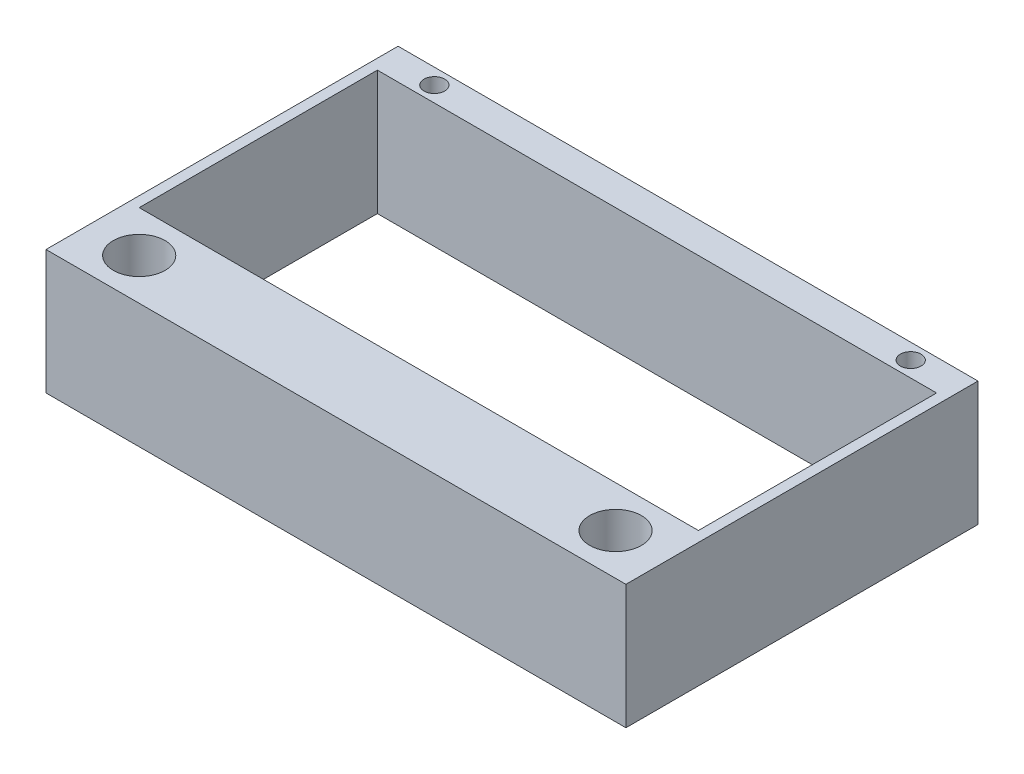
SolidWorks part; units mm, degrees
ref_plane "前视基准面" through (0, 0, 0) normal (0, 0, 1) x (1, 0, 0)
ref_plane "上视基准面" through (0, 0, 0) normal (0, 1, 0) x (1, 0, 0)
ref_plane "右视基准面" through (0, 0, 0) normal (1, 0, 0) x (0, 0, -1)
other "Configuration Table"
sketch "草图2" plane through (0, 0, 0) normal (0, 1, 0) x (1, 0, 0)
  line L0 (-10.7257, 9.9292) -> (45.2743, 9.9292)
  line L1 (45.2743, 9.9292) -> (45.2743, -22.0708)
  line L2 (45.2743, -22.0708) -> (-10.7257, -22.0708)
  line L3 (-10.7257, -22.0708) -> (-10.7257, -7.0708)
  line L5 (-9.7257, -7.0708) -> (-9.7257, -14.0708)
  line L6 (-9.7257, -14.0708) -> (44.2743, -14.0708)
  line L7 (44.2743, -14.0708) -> (44.2743, 8.9292)
  line L8 (44.2743, 8.9292) -> (-9.7257, 8.9292)
  line L9 (-9.7257, 8.9292) -> (-9.7257, 0.9292)
  line L11 (-10.7257, 1.9292) -> (-10.7257, 9.9292)
  line L12 (-10.7257, 1.9292) -> (-10.7257, -7.0708)
  line L13 (-9.7257, -7.0708) -> (-9.7257, 0.9292)
  dimension "D1" = 1
  dimension "D2" = 56
  dimension "D3" = 32
  dimension "D4" = 8
  dimension "D5" = 1
  dimension "D7" = 54
extrude "凸台-拉伸1" add sketch "草图2" along normal blind 12
ref_plane "基准面1" through (0, 12, 0) normal (0, 1, 0) x (1, 0, 0)
sketch "草图4" plane through (0, 0, 0) normal (0, 1, 0) x (1, 0, 0)
  line L1 (-10.7257, 9.9292) -> (45.2743, 9.9292)
  line L2 (-10.7257, 9.9292) -> (-10.7257, 11.9292)
  line L3 (-10.7257, 11.9292) -> (45.2743, 11.9292)
  line L4 (45.2743, 9.9292) -> (45.2743, 11.9292)
  dimension "D1" = 2
extrude "凸台-拉伸2" add sketch "草图4" along normal blind 12
sketch "草图3" plane through (0, 12, 0) normal (0, 1, 0) x (1, 0, 0)
  line L0 (-10.7257, 11.9292) -> (-10.7257, -22.0708) construction
  line L9 (45.2743, 11.9292) -> (-10.7257, 11.9292) construction
  line L10 (45.2743, -22.0708) -> (45.2743, 11.9292) construction
  line L12 (-10.7257, -22.0708) -> (45.2743, -22.0708) construction
  line L13 (-3.876, -14.0708) -> (-3.876, -22.0708) construction
  line L14 (-9.7257, -14.0708) -> (44.2743, -14.0708) construction
  line L15 (-3.876, -18.0708) -> (-9.3766, -18.0708) construction
  line L16 (-10.7257, 11.9292) -> (-10.7257, -22.0708) construction
  line L17 (45.2743, -22.0708) -> (45.2743, 11.9292) construction
  circle A3 centre (-5.7257, -18.0708) radius 2.5
  circle A4 centre (40.2743, -18.0708) radius 2.5
  circle A5 centre (-5.7257, 10.4292) radius 1
  circle A6 centre (40.2743, 10.4292) radius 1
  dimension "D2" = 5
  dimension "D5" = 5
  dimension "D1" = 5
  dimension "D3" = 5
  dimension "D4" = 1.5
  dimension "D6" = 1.5
extrude "切除-拉伸1" cut sketch "草图3" against normal through all
